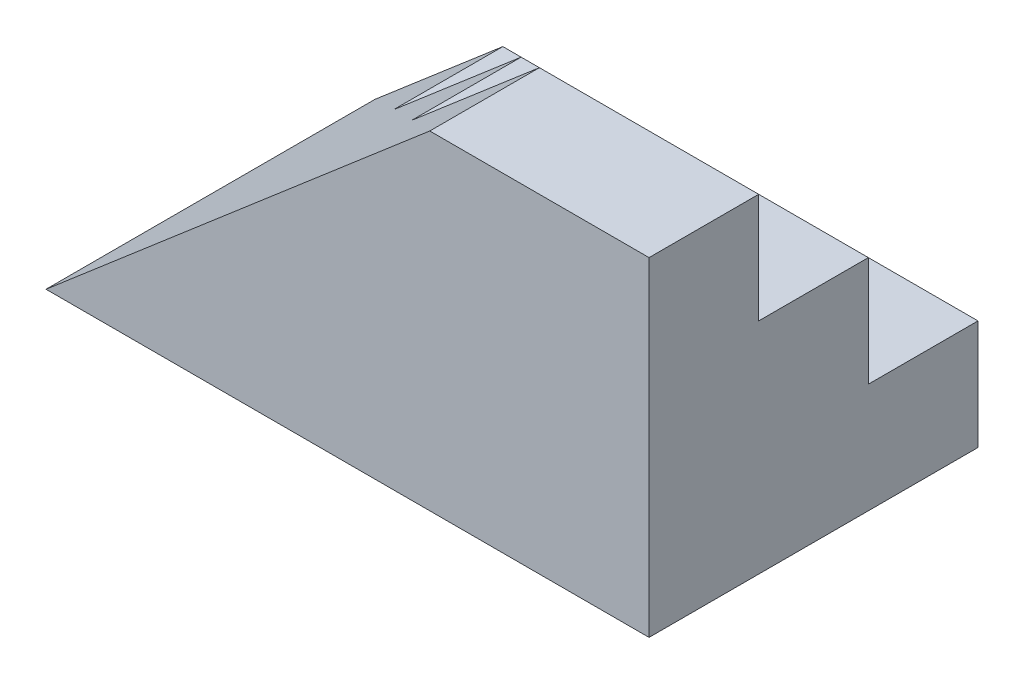
SolidWorks part; units mm, degrees
material "Ductile Iron"
ref_plane "Front Plane" through (0, 0, 0) normal (0, 0, 1) x (1, 0, 0)
ref_plane "Top Plane" through (0, 0, 0) normal (0, 1, 0) x (1, 0, 0)
ref_plane "Right Plane" through (0, 0, 0) normal (1, 0, 0) x (0, 0, -1)
sketch "Croquis1" plane through (0, 0, 0) normal (1, 0, 0) x (0, 0, -1)
  line L0 (0, 0) -> (60, 0)
  line L1 (0, 0) -> (0, 60)
  line L2 (20, 60) -> (20, 40)
  line L3 (20, 40) -> (40, 40)
  line L4 (40, 40) -> (40, 20)
  line L5 (40, 20) -> (60, 20)
  line L6 (60, 20) -> (60, 0)
  line L8 (0, 60) -> (20, 60)
  dimension "D1" = 20
  dimension "D2" = 20
  dimension "D3" = 20
  dimension "D4" = 20
  dimension "D5" = 20
  dimension "D6" = 20
extrude "Saliente-Extruir2" add sketch "Croquis1" along normal blind 110
sketch "Croquis2" plane through (0, 0, 0) normal (0, 0, 1) x (1, 0, 0)
  line L0 (0, 0) -> (70, 60)
  line L1 (110, 60) -> (0, 60) construction
  line L2 (110, 60) -> (110, 0) construction
  dimension "D1" = 40
extrude "Cortar-Extruir1" cut sketch "Croquis2" against normal through all both and the other way through all
